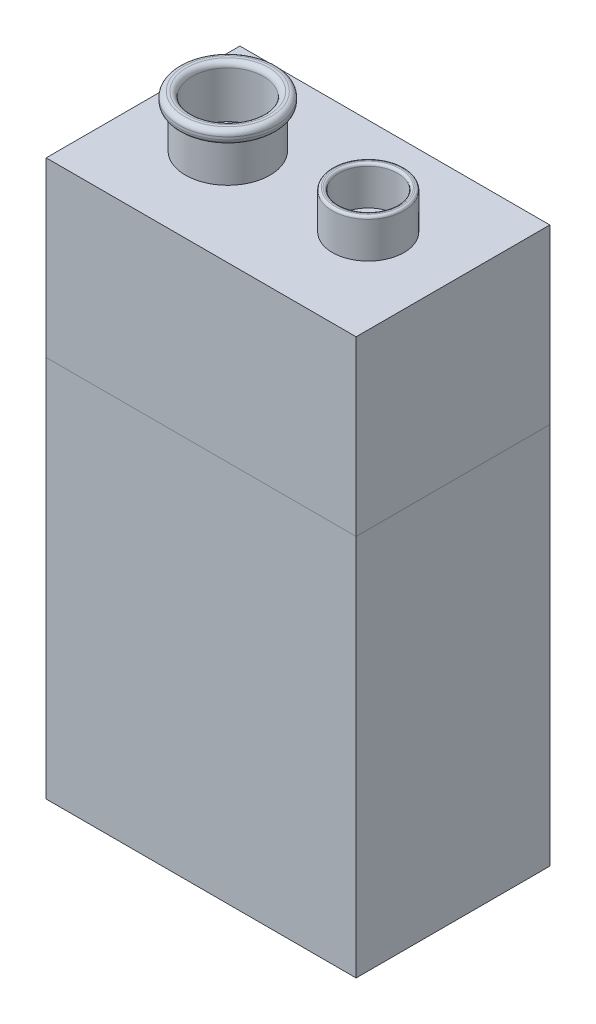
SolidWorks part; units mm, degrees
ref_plane "Alzado" through (0, 0, 0) normal (0, 0, 1) x (1, 0, 0)
ref_plane "Planta" through (0, 0, 0) normal (0, 1, 0) x (1, 0, 0)
ref_plane "Vista lateral" through (0, 0, 0) normal (1, 0, 0) x (0, 0, -1)
sketch "Croquis1" plane through (0, 0, 0) normal (0, 1, 0) x (1, 0, 0)
  line L1 (0, 0) -> (24, 0)
  line L2 (0, 0) -> (0, 15)
  line L3 (0, 15) -> (24, 15)
  line L4 (24, 0) -> (24, 15)
  dimension "D1" = 15
  dimension "D2" = 24
extrude "Saliente-Extruir1" add sketch "Croquis1" along normal blind 43
sketch "Croquis2" plane through (0, 43, 0) normal (0, 1, 0) x (1, 0, 0)
  line L0 (12, 15) -> (12, 0) construction
  line L1 (24, 15) -> (0, 15) construction
  line L2 (0, 0) -> (24, 0) construction
  line L3 (6.5616, 7.5) -> (12, 7.5) construction
  circle A0 centre (6.5616, 7.5) radius 2.7717
  circle A1 centre (17.4384, 7.5) radius 2.7717
  circle A2 centre (6.5616, 7.5) radius 3.2717
  circle A3 centre (17.4384, 7.5) radius 2.2717
  dimension "D1" = 0.5
  dimension "D2" = 0.5
extrude "Saliente-Extruir2" add sketch "Croquis2" along normal blind 3
sketch "Croquis3" plane through (0, 46, 0) normal (0, 1, 0) x (1, 0, 0)
  circle A0 centre (6.5616, 7.5) radius 2.7717 construction
  circle A1 centre (6.5616, 7.5) radius 2.7717
  circle A4 centre (6.5616, 7.5) radius 3.7717
  circle A5 centre (6.5616, 7.5) radius 3.7717
  dimension "D1" = 0.5
extrude "Saliente-Extruir3" add sketch "Croquis3" along normal blind 1
fillet "Redondeo1" radius 0.4 3 edges at (6.5616, 46, -3.7283) (6.5616, 47, -3.7283) (6.5616, 47, -4.7283)
fillet "Redondeo2" radius 0.2 2 edges at (17.4384, 46, -10.2717) (17.4384, 46, -9.7717)
sketch "Croquis4" plane through (0, 0, 0) normal (0, 0, 1) x (1, 0, 0)
  line L0 (-3.2614, 29.6108) -> (29.3087, 29.6108)
split line "Línea de partición1"
